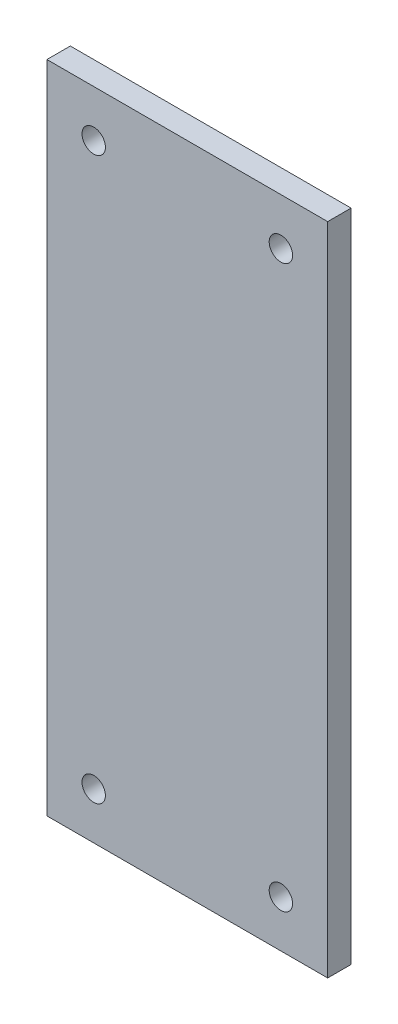
SolidWorks part; units mm, degrees
ref_plane "Front Plane" through (0, 0, 0) normal (0, 0, 1) x (1, 0, 0)
ref_plane "Top Plane" through (0, 0, 0) normal (0, 1, 0) x (1, 0, 0)
ref_plane "Right Plane" through (0, 0, 0) normal (1, 0, 0) x (0, 0, -1)
sketch "Sketch1" plane through (0, 0, 0) normal (0, 0, 1) x (1, 0, 0)
  line L1 (-149.1631, 44.45) -> (-72.9631, 44.45)
  line L2 (-149.1631, 44.45) -> (-149.1631, -133.35)
  line L3 (-149.1631, -133.35) -> (-72.9631, -133.35)
  line L4 (-72.9631, 44.45) -> (-72.9631, -133.35)
  circle A0 centre (-85.6631, -120.65) radius 3.175
  circle A1 centre (-136.4631, -120.65) radius 3.175
  circle A2 centre (-85.6631, 31.75) radius 3.175
  circle A3 centre (-136.4631, 31.75) radius 3.175
extrude "Boss-Extrude1" add sketch "Sketch1" along normal blind 6.35
